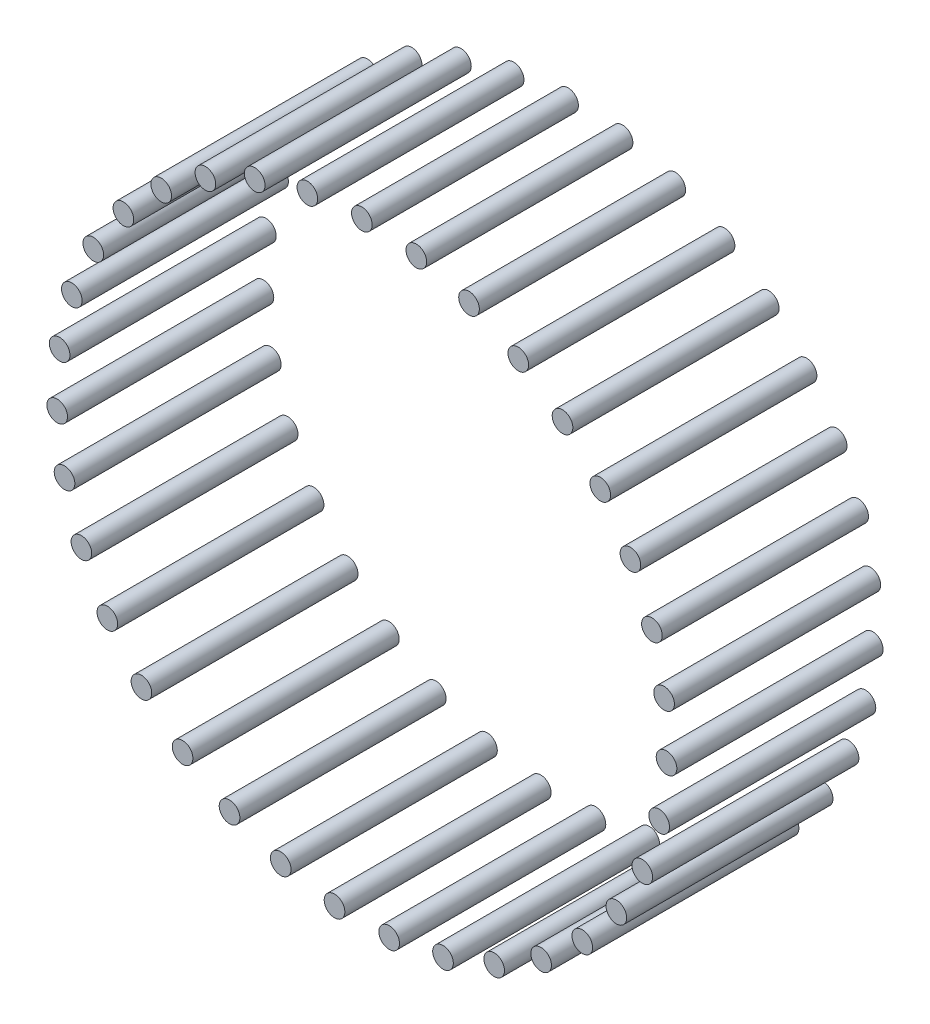
SolidWorks part; units mm, degrees
ref_plane "Спереди" through (0, 0, 0) normal (0, 0, 1) x (1, 0, 0)
ref_plane "Сверху" through (0, 0, 0) normal (0, 1, 0) x (1, 0, 0)
ref_plane "Справа" through (0, 0, 0) normal (1, 0, 0) x (0, 0, -1)
sketch "Эскиз1" plane through (0, 0, 0) normal (0, 0, 1) x (1, 0, 0)
  line L0 (0, 0) -> (0, 50000) construction
  circle A1 centre (0, 0) radius 51.75 construction
  circle A2 centre (0, 51.75) radius 1.75
  circle A3 centre (9.2403, 50.9184) radius 1.75
  circle A4 centre (18.1836, 48.4502) radius 1.75
  circle A5 centre (26.5425, 44.4247) radius 1.75
  circle A6 centre (34.0483, 38.9714) radius 1.75
  circle A7 centre (40.4598, 32.2656) radius 1.75
  circle A8 centre (45.5708, 24.5227) radius 1.75
  circle A9 centre (49.2172, 15.9916) radius 1.75
  circle A10 centre (51.2817, 6.9466) radius 1.75
  circle A11 centre (51.6979, -2.3218) radius 1.75
  circle A12 centre (50.4525, -11.5155) radius 1.75
  circle A13 centre (47.5856, -20.339) radius 1.75
  circle A14 centre (43.1892, -28.5089) radius 1.75
  circle A15 centre (37.4046, -35.7625) radius 1.75
  circle A16 centre (30.4179, -41.8666) radius 1.75
  circle A17 centre (22.4535, -46.6251) radius 1.75
  circle A18 centre (13.7674, -49.8851) radius 1.75
  circle A19 centre (4.6388, -51.5417) radius 1.75
  circle A20 centre (-4.6388, -51.5417) radius 1.75
  circle A21 centre (-13.7674, -49.8851) radius 1.75
  circle A22 centre (-22.4535, -46.6251) radius 1.75
  circle A23 centre (-30.4179, -41.8666) radius 1.75
  circle A24 centre (-37.4046, -35.7625) radius 1.75
  circle A25 centre (-43.1892, -28.5089) radius 1.75
  circle A26 centre (-47.5856, -20.339) radius 1.75
  circle A27 centre (-50.4525, -11.5155) radius 1.75
  circle A28 centre (-51.6979, -2.3218) radius 1.75
  circle A29 centre (-51.2817, 6.9466) radius 1.75
  circle A30 centre (-49.2172, 15.9916) radius 1.75
  circle A31 centre (-45.5708, 24.5227) radius 1.75
  circle A32 centre (-40.4598, 32.2656) radius 1.75
  circle A33 centre (-34.0483, 38.9714) radius 1.75
  circle A34 centre (-26.5425, 44.4247) radius 1.75
  circle A35 centre (-18.1836, 48.4502) radius 1.75
  circle A36 centre (-9.2403, 50.9184) radius 1.75
  point P78 (0, 0)
  dimension "D1" = 3.5
  dimension "D2" = 103.5
  dimension "D5" = 10.286
  dimension "D6" = 3.5
  dimension "D4" = 51.75
  dimension "D3" = 35
extrude "Бобышка-Вытянуть1" add sketch "Эскиз1" along normal blind 35
